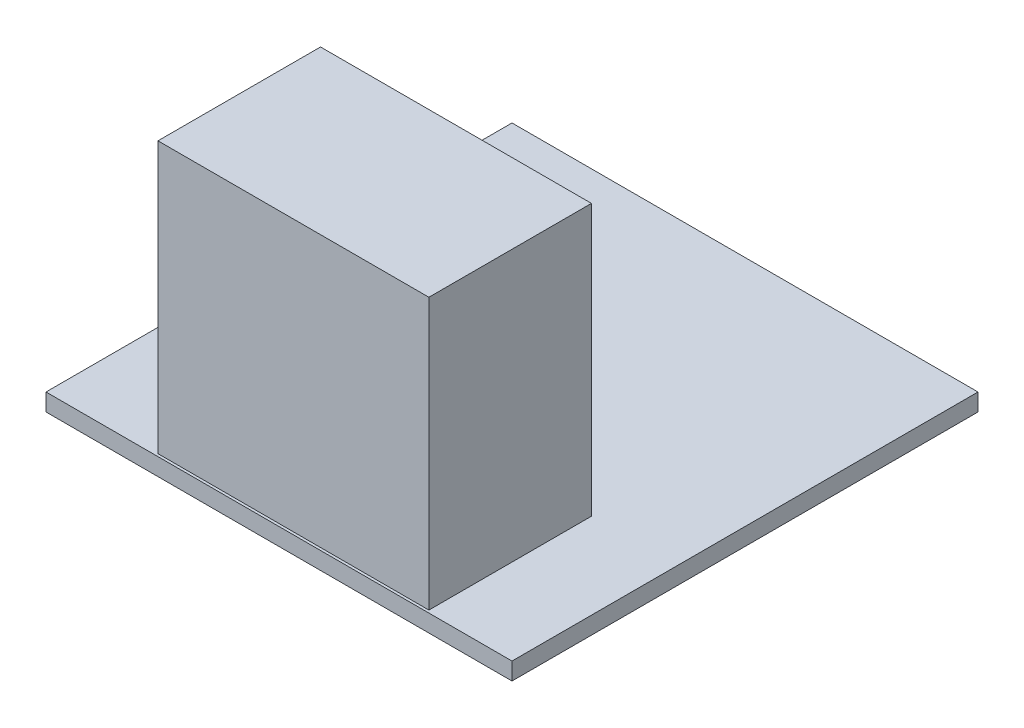
SolidWorks part; units mm, degrees
ref_plane "Front Plane" through (0, 0, 0) normal (0, 0, 1) x (1, 0, 0)
ref_plane "Top Plane" through (0, 0, 0) normal (0, 1, 0) x (1, 0, 0)
ref_plane "Right Plane" through (0, 0, 0) normal (1, 0, 0) x (0, 0, -1)
sketch "Sketch1" plane through (0, 0, 0) normal (0, 1, 0) x (1, 0, 0)
  line L1 (0, 0) -> (43, 0)
  line L2 (0, 0) -> (0, 43)
  line L3 (0, 43) -> (43, 43)
  line L4 (43, 0) -> (43, 43)
  dimension "D1" = 43
  dimension "D2" = 43
extrude "Boss-Extrude1" add sketch "Sketch1" along normal blind 1.6
sketch "Sketch2" plane through (0, 1.6, 0) normal (0, 1, 0) x (1, 0, 0)
  line L1 (10.0945, 0.237) -> (35.0945, 0.237)
  line L2 (10.0945, 0.237) -> (10.0945, 15.237)
  line L3 (10.0945, 15.237) -> (35.0945, 15.237)
  line L4 (35.0945, 0.237) -> (35.0945, 15.237)
  dimension "D1" = 25
  dimension "D2" = 15
extrude "Boss-Extrude2" add sketch "Sketch2" along normal blind 25
